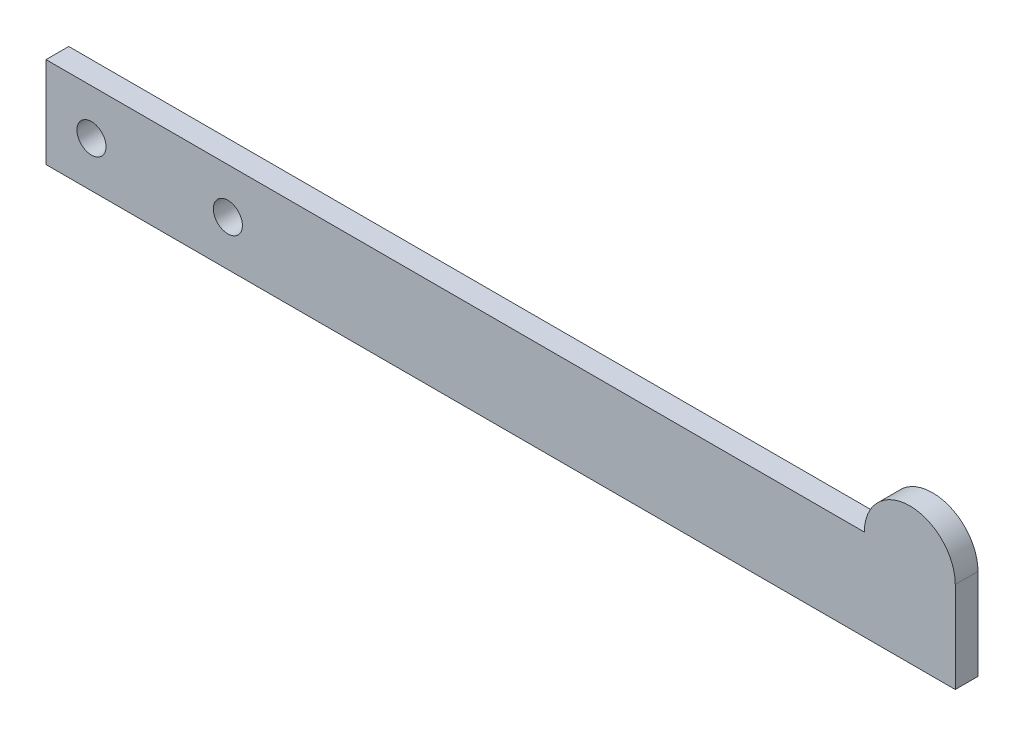
SolidWorks part; units mm, degrees
ref_plane "Front Plane" through (0, 0, 0) normal (0, 0, 1) x (1, 0, 0)
ref_plane "Top Plane" through (0, 0, 0) normal (0, 1, 0) x (1, 0, 0)
ref_plane "Right Plane" through (0, 0, 0) normal (1, 0, 0) x (0, 0, -1)
sketch "Sketch1" plane through (0, 0, 0) normal (0, 0, 1) x (1, 0, 0)
  line L1 (63.5, -6.35) -> (-63.5, -6.35)
  line L2 (63.5, -6.35) -> (63.5, 6.35)
  line L3 (63.5, 6.35) -> (-63.5, 6.35)
  line L4 (-63.5, -6.35) -> (-63.5, 6.35)
  line L5 (63.5, -6.35) -> (-63.5, 6.35) construction
  line L6 (63.5, 6.35) -> (-63.5, -6.35) construction
  circle A0 centre (-57.15, 0) radius 2.032
  circle A1 centre (-38.1, 0) radius 2.032
  point P0 (0, 0)
  dimension "D5" = 4.064
  dimension "D1" = 12.7
  dimension "D2" = 127
  dimension "D3" = 6.35
  dimension "D4" = 19.05
extrude "Boss-Extrude1" add sketch "Sketch1" along normal blind 3.175
sketch "Sketch2" plane through (0, 0, 3.175) normal (0, 0, 1) x (1, 0, 0)
  line L0 (63.5, 6.35) -> (-63.5, 6.35) construction
  line L1 (63.5, 6.35) -> (50.8, 6.35)
  arc A0 (50.8, 6.35) -> (63.5, 6.35) centre (57.15, 6.35) cw
  point P5 (12.444, -2.9512)
  dimension "D1" = 6.35
extrude "Boss-Extrude2" add sketch "Sketch2" against normal blind 3.175
